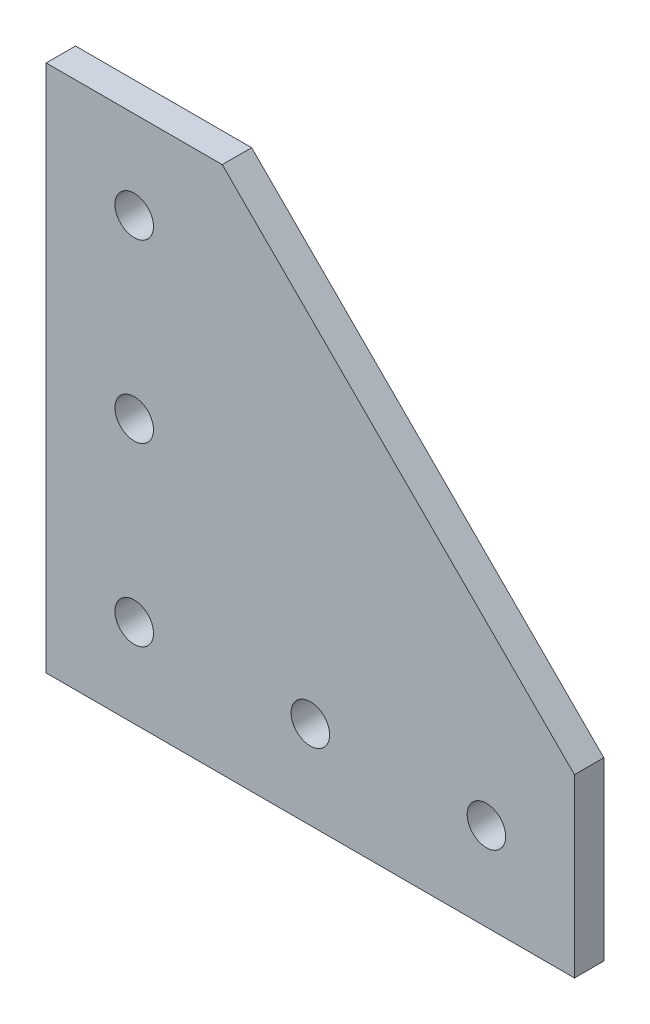
SolidWorks part; units mm, degrees
ref_plane "Front Plane" through (0, 0, 0) normal (0, 0, 1) x (1, 0, 0)
ref_plane "Top Plane" through (0, 0, 0) normal (0, 1, 0) x (1, 0, 0)
ref_plane "Right Plane" through (0, 0, 0) normal (1, 0, 0) x (0, 0, -1)
sketch "Sketch1" plane through (0, 0, 0) normal (0, 0, 1) x (1, 0, 0)
  line L0 (0, 0) -> (0, 114.3)
  line L1 (19.05, 19.05) -> (57.15, 19.05) construction
  line L2 (57.15, 19.05) -> (95.25, 19.05) construction
  line L3 (19.05, 19.05) -> (19.05, 57.15) construction
  line L4 (114.3, 38.1) -> (38.1, 114.3)
  line L5 (114.3, 0) -> (0, 0)
  line L6 (19.05, 57.15) -> (19.05, 95.25) construction
  line L7 (114.3, 38.1) -> (114.3, 0)
  line L8 (0, 114.3) -> (38.1, 114.3)
  circle A0 centre (19.05, 19.05) radius 4.1656
  circle A1 centre (57.15, 19.05) radius 4.1656
  circle A2 centre (95.25, 19.05) radius 4.1656
  circle A3 centre (19.05, 57.15) radius 4.1656
  circle A4 centre (19.05, 95.25) radius 4.1656
  dimension "D1" = 38.1
  dimension "E" = 8.3312
  dimension "D2" = 19.05
  dimension "C" = 38.1
  dimension "D3" = 19.05
  dimension "B" = 114.3
extrude "Boss-Extrude1" add sketch "Sketch1" along normal mid plane 6.35
